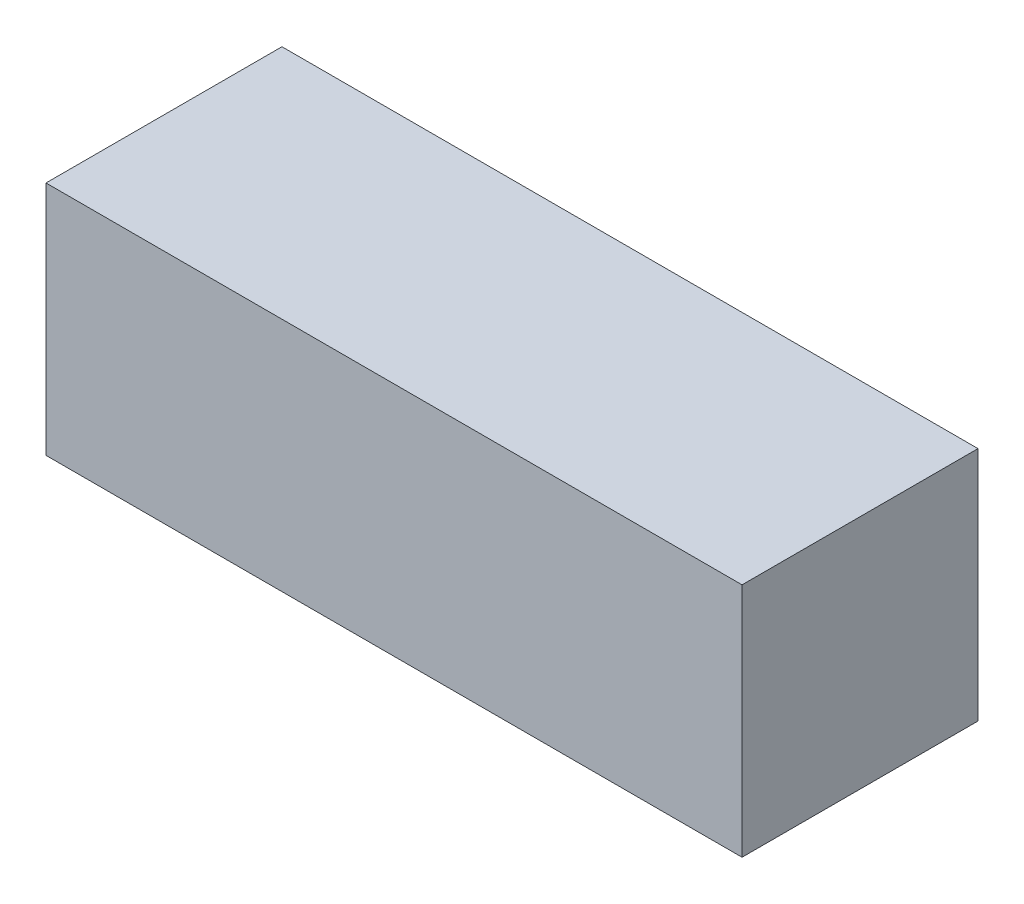
SolidWorks part; units mm, degrees
ref_plane "前视基准面" through (0, 0, 0) normal (0, 0, 1) x (1, 0, 0)
ref_plane "上视基准面" through (0, 0, 0) normal (0, 1, 0) x (1, 0, 0)
ref_plane "右视基准面" through (0, 0, 0) normal (1, 0, 0) x (0, 0, -1)
sketch "草图1" plane through (0, 0, 0) normal (0, 1, 0) x (1, 0, 0)
  line L1 (29.5, -10) -> (-29.5, -10)
  line L2 (29.5, -10) -> (29.5, 10)
  line L3 (29.5, 10) -> (-29.5, 10)
  line L4 (-29.5, -10) -> (-29.5, 10)
  line L5 (29.5, -10) -> (-29.5, 10) construction
  line L6 (29.5, 10) -> (-29.5, -10) construction
  point P0 (0, 0)
  dimension "D1" = 59
  dimension "D2" = 20
extrude "凸台-拉伸1" add sketch "草图1" along normal blind 20
